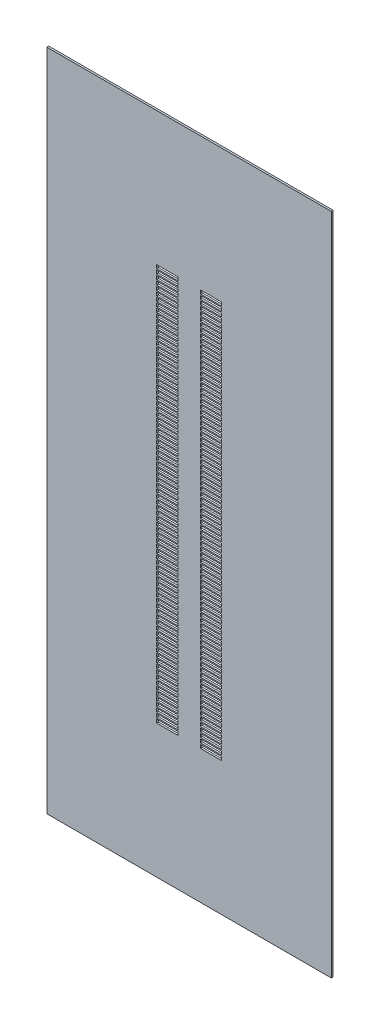
SolidWorks part; units mm, degrees
ref_plane "Front Plane" through (0, 0, 0) normal (0, 0, 1) x (1, 0, 0)
ref_plane "Top Plane" through (0, 0, 0) normal (0, 1, 0) x (1, 0, 0)
ref_plane "Right Plane" through (0, 0, 0) normal (1, 0, 0) x (0, 0, -1)
sketch "Sketch1" plane through (0, 0, 0) normal (0, 0, 1) x (1, 0, 0)
  line L1340 (-1.19, -0.37) -> (-1.19, 0)
  line L1341 (-1.19, 0) -> (-3.41, 0)
  line L1342 (-3.41, 0) -> (-3.41, -0.37)
  line L1343 (-3.41, -0.37) -> (-1.19, -0.37)
  line L2016 (-1.19, 0) -> (1.19, 0) construction
  line L2017 (0, 0) -> (0, -41.87) construction
  line L2018 (1.19, -0.37) -> (1.19, 0)
  line L2019 (3.41, -0.37) -> (1.19, -0.37)
  line L2020 (3.41, 0) -> (3.41, -0.37)
  line L2021 (1.19, 0) -> (3.41, 0)
  line L2022 (1.19, -0.5) -> (3.41, -0.5)
  line L2023 (3.41, -0.5) -> (3.41, -0.87)
  line L2024 (3.41, -0.87) -> (1.19, -0.87)
  line L2025 (1.19, -0.87) -> (1.19, -0.5)
  line L2026 (-1.19, -0.5) -> (-3.41, -0.5)
  line L2027 (-3.41, -0.5) -> (-3.41, -0.87)
  line L2028 (-3.41, -0.87) -> (-1.19, -0.87)
  line L2029 (-1.19, -0.87) -> (-1.19, -0.5)
  line L2030 (1.19, -1) -> (3.41, -1)
  line L2031 (3.41, -1) -> (3.41, -1.37)
  line L2032 (3.41, -1.37) -> (1.19, -1.37)
  line L2033 (1.19, -1.37) -> (1.19, -1)
  line L2034 (-1.19, -1) -> (-3.41, -1)
  line L2035 (-3.41, -1) -> (-3.41, -1.37)
  line L2036 (-3.41, -1.37) -> (-1.19, -1.37)
  line L2037 (-1.19, -1.37) -> (-1.19, -1)
  line L2038 (1.19, -1.5) -> (3.41, -1.5)
  line L2039 (3.41, -1.5) -> (3.41, -1.87)
  line L2040 (3.41, -1.87) -> (1.19, -1.87)
  line L2041 (1.19, -1.87) -> (1.19, -1.5)
  line L2042 (-1.19, -1.5) -> (-3.41, -1.5)
  line L2043 (-3.41, -1.5) -> (-3.41, -1.87)
  line L2044 (-3.41, -1.87) -> (-1.19, -1.87)
  line L2045 (-1.19, -1.87) -> (-1.19, -1.5)
  line L2046 (1.19, -2) -> (3.41, -2)
  line L2047 (3.41, -2) -> (3.41, -2.37)
  line L2048 (3.41, -2.37) -> (1.19, -2.37)
  line L2049 (1.19, -2.37) -> (1.19, -2)
  line L2050 (-1.19, -2) -> (-3.41, -2)
  line L2051 (-3.41, -2) -> (-3.41, -2.37)
  line L2052 (-3.41, -2.37) -> (-1.19, -2.37)
  line L2053 (-1.19, -2.37) -> (-1.19, -2)
  line L2054 (1.19, -2.5) -> (3.41, -2.5)
  line L2055 (3.41, -2.5) -> (3.41, -2.87)
  line L2056 (3.41, -2.87) -> (1.19, -2.87)
  line L2057 (1.19, -2.87) -> (1.19, -2.5)
  line L2058 (-1.19, -2.5) -> (-3.41, -2.5)
  line L2059 (-3.41, -2.5) -> (-3.41, -2.87)
  line L2060 (-3.41, -2.87) -> (-1.19, -2.87)
  line L2061 (-1.19, -2.87) -> (-1.19, -2.5)
  line L2062 (1.19, -3) -> (3.41, -3)
  line L2063 (3.41, -3) -> (3.41, -3.37)
  line L2064 (3.41, -3.37) -> (1.19, -3.37)
  line L2065 (1.19, -3.37) -> (1.19, -3)
  line L2066 (-1.19, -3) -> (-3.41, -3)
  line L2067 (-3.41, -3) -> (-3.41, -3.37)
  line L2068 (-3.41, -3.37) -> (-1.19, -3.37)
  line L2069 (-1.19, -3.37) -> (-1.19, -3)
  line L2070 (1.19, -3.5) -> (3.41, -3.5)
  line L2071 (3.41, -3.5) -> (3.41, -3.87)
  line L2072 (3.41, -3.87) -> (1.19, -3.87)
  line L2073 (1.19, -3.87) -> (1.19, -3.5)
  line L2074 (-1.19, -3.5) -> (-3.41, -3.5)
  line L2075 (-3.41, -3.5) -> (-3.41, -3.87)
  line L2076 (-3.41, -3.87) -> (-1.19, -3.87)
  line L2077 (-1.19, -3.87) -> (-1.19, -3.5)
  line L2078 (1.19, -4) -> (3.41, -4)
  line L2079 (3.41, -4) -> (3.41, -4.37)
  line L2080 (3.41, -4.37) -> (1.19, -4.37)
  line L2081 (1.19, -4.37) -> (1.19, -4)
  line L2082 (-1.19, -4) -> (-3.41, -4)
  line L2083 (-3.41, -4) -> (-3.41, -4.37)
  line L2084 (-3.41, -4.37) -> (-1.19, -4.37)
  line L2085 (-1.19, -4.37) -> (-1.19, -4)
  line L2086 (1.19, -4.5) -> (3.41, -4.5)
  line L2087 (3.41, -4.5) -> (3.41, -4.87)
  line L2088 (3.41, -4.87) -> (1.19, -4.87)
  line L2089 (1.19, -4.87) -> (1.19, -4.5)
  line L2090 (-1.19, -4.5) -> (-3.41, -4.5)
  line L2091 (-3.41, -4.5) -> (-3.41, -4.87)
  line L2092 (-3.41, -4.87) -> (-1.19, -4.87)
  line L2093 (-1.19, -4.87) -> (-1.19, -4.5)
  line L2094 (1.19, -5) -> (3.41, -5)
  line L2095 (3.41, -5) -> (3.41, -5.37)
  line L2096 (3.41, -5.37) -> (1.19, -5.37)
  line L2097 (1.19, -5.37) -> (1.19, -5)
  line L2098 (-1.19, -5) -> (-3.41, -5)
  line L2099 (-3.41, -5) -> (-3.41, -5.37)
  line L2100 (-3.41, -5.37) -> (-1.19, -5.37)
  line L2101 (-1.19, -5.37) -> (-1.19, -5)
  line L2102 (1.19, -5.5) -> (3.41, -5.5)
  line L2103 (3.41, -5.5) -> (3.41, -5.87)
  line L2104 (3.41, -5.87) -> (1.19, -5.87)
  line L2105 (1.19, -5.87) -> (1.19, -5.5)
  line L2106 (-1.19, -5.5) -> (-3.41, -5.5)
  line L2107 (-3.41, -5.5) -> (-3.41, -5.87)
  line L2108 (-3.41, -5.87) -> (-1.19, -5.87)
  line L2109 (-1.19, -5.87) -> (-1.19, -5.5)
  line L2110 (1.19, -6) -> (3.41, -6)
  line L2111 (3.41, -6) -> (3.41, -6.37)
  line L2112 (3.41, -6.37) -> (1.19, -6.37)
  line L2113 (1.19, -6.37) -> (1.19, -6)
  line L2114 (-1.19, -6) -> (-3.41, -6)
  line L2115 (-3.41, -6) -> (-3.41, -6.37)
  line L2116 (-3.41, -6.37) -> (-1.19, -6.37)
  line L2117 (-1.19, -6.37) -> (-1.19, -6)
  line L2118 (1.19, -6.5) -> (3.41, -6.5)
  line L2119 (3.41, -6.5) -> (3.41, -6.87)
  line L2120 (3.41, -6.87) -> (1.19, -6.87)
  line L2121 (1.19, -6.87) -> (1.19, -6.5)
  line L2122 (-1.19, -6.5) -> (-3.41, -6.5)
  line L2123 (-3.41, -6.5) -> (-3.41, -6.87)
  line L2124 (-3.41, -6.87) -> (-1.19, -6.87)
  line L2125 (-1.19, -6.87) -> (-1.19, -6.5)
  line L2126 (1.19, -7) -> (3.41, -7)
  line L2127 (3.41, -7) -> (3.41, -7.37)
  line L2128 (3.41, -7.37) -> (1.19, -7.37)
  line L2129 (1.19, -7.37) -> (1.19, -7)
  line L2130 (-1.19, -7) -> (-3.41, -7)
  line L2131 (-3.41, -7) -> (-3.41, -7.37)
  line L2132 (-3.41, -7.37) -> (-1.19, -7.37)
  line L2133 (-1.19, -7.37) -> (-1.19, -7)
  line L2134 (1.19, -7.5) -> (3.41, -7.5)
  line L2135 (3.41, -7.5) -> (3.41, -7.87)
  line L2136 (3.41, -7.87) -> (1.19, -7.87)
  line L2137 (1.19, -7.87) -> (1.19, -7.5)
  line L2138 (-1.19, -7.5) -> (-3.41, -7.5)
  line L2139 (-3.41, -7.5) -> (-3.41, -7.87)
  line L2140 (-3.41, -7.87) -> (-1.19, -7.87)
  line L2141 (-1.19, -7.87) -> (-1.19, -7.5)
  line L2142 (1.19, -8) -> (3.41, -8)
  line L2143 (3.41, -8) -> (3.41, -8.37)
  line L2144 (3.41, -8.37) -> (1.19, -8.37)
  line L2145 (1.19, -8.37) -> (1.19, -8)
  line L2146 (-1.19, -8) -> (-3.41, -8)
  line L2147 (-3.41, -8) -> (-3.41, -8.37)
  line L2148 (-3.41, -8.37) -> (-1.19, -8.37)
  line L2149 (-1.19, -8.37) -> (-1.19, -8)
  line L2150 (1.19, -8.5) -> (3.41, -8.5)
  line L2151 (3.41, -8.5) -> (3.41, -8.87)
  line L2152 (3.41, -8.87) -> (1.19, -8.87)
  line L2153 (1.19, -8.87) -> (1.19, -8.5)
  line L2154 (-1.19, -8.5) -> (-3.41, -8.5)
  line L2155 (-3.41, -8.5) -> (-3.41, -8.87)
  line L2156 (-3.41, -8.87) -> (-1.19, -8.87)
  line L2157 (-1.19, -8.87) -> (-1.19, -8.5)
  line L2158 (1.19, -9) -> (3.41, -9)
  line L2159 (3.41, -9) -> (3.41, -9.37)
  line L2160 (3.41, -9.37) -> (1.19, -9.37)
  line L2161 (1.19, -9.37) -> (1.19, -9)
  line L2162 (-1.19, -9) -> (-3.41, -9)
  line L2163 (-3.41, -9) -> (-3.41, -9.37)
  line L2164 (-3.41, -9.37) -> (-1.19, -9.37)
  line L2165 (-1.19, -9.37) -> (-1.19, -9)
  line L2166 (1.19, -9.5) -> (3.41, -9.5)
  line L2167 (3.41, -9.5) -> (3.41, -9.87)
  line L2168 (3.41, -9.87) -> (1.19, -9.87)
  line L2169 (1.19, -9.87) -> (1.19, -9.5)
  line L2170 (-1.19, -9.5) -> (-3.41, -9.5)
  line L2171 (-3.41, -9.5) -> (-3.41, -9.87)
  line L2172 (-3.41, -9.87) -> (-1.19, -9.87)
  line L2173 (-1.19, -9.87) -> (-1.19, -9.5)
  line L2174 (1.19, -10) -> (3.41, -10)
  line L2175 (3.41, -10) -> (3.41, -10.37)
  line L2176 (3.41, -10.37) -> (1.19, -10.37)
  line L2177 (1.19, -10.37) -> (1.19, -10)
  line L2178 (-1.19, -10) -> (-3.41, -10)
  line L2179 (-3.41, -10) -> (-3.41, -10.37)
  line L2180 (-3.41, -10.37) -> (-1.19, -10.37)
  line L2181 (-1.19, -10.37) -> (-1.19, -10)
  line L2182 (1.19, -10.5) -> (3.41, -10.5)
  line L2183 (3.41, -10.5) -> (3.41, -10.87)
  line L2184 (3.41, -10.87) -> (1.19, -10.87)
  line L2185 (1.19, -10.87) -> (1.19, -10.5)
  line L2186 (-1.19, -10.5) -> (-3.41, -10.5)
  line L2187 (-3.41, -10.5) -> (-3.41, -10.87)
  line L2188 (-3.41, -10.87) -> (-1.19, -10.87)
  line L2189 (-1.19, -10.87) -> (-1.19, -10.5)
  line L2190 (1.19, -11) -> (3.41, -11)
  line L2191 (3.41, -11) -> (3.41, -11.37)
  line L2192 (3.41, -11.37) -> (1.19, -11.37)
  line L2193 (1.19, -11.37) -> (1.19, -11)
  line L2194 (-1.19, -11) -> (-3.41, -11)
  line L2195 (-3.41, -11) -> (-3.41, -11.37)
  line L2196 (-3.41, -11.37) -> (-1.19, -11.37)
  line L2197 (-1.19, -11.37) -> (-1.19, -11)
  line L2198 (1.19, -11.5) -> (3.41, -11.5)
  line L2199 (3.41, -11.5) -> (3.41, -11.87)
  line L2200 (3.41, -11.87) -> (1.19, -11.87)
  line L2201 (1.19, -11.87) -> (1.19, -11.5)
  line L2202 (-1.19, -11.5) -> (-3.41, -11.5)
  line L2203 (-3.41, -11.5) -> (-3.41, -11.87)
  line L2204 (-3.41, -11.87) -> (-1.19, -11.87)
  line L2205 (-1.19, -11.87) -> (-1.19, -11.5)
  line L2206 (1.19, -12) -> (3.41, -12)
  line L2207 (3.41, -12) -> (3.41, -12.37)
  line L2208 (3.41, -12.37) -> (1.19, -12.37)
  line L2209 (1.19, -12.37) -> (1.19, -12)
  line L2210 (-1.19, -12) -> (-3.41, -12)
  line L2211 (-3.41, -12) -> (-3.41, -12.37)
  line L2212 (-3.41, -12.37) -> (-1.19, -12.37)
  line L2213 (-1.19, -12.37) -> (-1.19, -12)
  line L2214 (1.19, -12.5) -> (3.41, -12.5)
  line L2215 (3.41, -12.5) -> (3.41, -12.87)
  line L2216 (3.41, -12.87) -> (1.19, -12.87)
  line L2217 (1.19, -12.87) -> (1.19, -12.5)
  line L2218 (-1.19, -12.5) -> (-3.41, -12.5)
  line L2219 (-3.41, -12.5) -> (-3.41, -12.87)
  line L2220 (-3.41, -12.87) -> (-1.19, -12.87)
  line L2221 (-1.19, -12.87) -> (-1.19, -12.5)
  line L2222 (1.19, -13) -> (3.41, -13)
  line L2223 (3.41, -13) -> (3.41, -13.37)
  line L2224 (3.41, -13.37) -> (1.19, -13.37)
  line L2225 (1.19, -13.37) -> (1.19, -13)
  line L2226 (-1.19, -13) -> (-3.41, -13)
  line L2227 (-3.41, -13) -> (-3.41, -13.37)
  line L2228 (-3.41, -13.37) -> (-1.19, -13.37)
  line L2229 (-1.19, -13.37) -> (-1.19, -13)
  line L2230 (1.19, -13.5) -> (3.41, -13.5)
  line L2231 (3.41, -13.5) -> (3.41, -13.87)
  line L2232 (3.41, -13.87) -> (1.19, -13.87)
  line L2233 (1.19, -13.87) -> (1.19, -13.5)
  line L2234 (-1.19, -13.5) -> (-3.41, -13.5)
  line L2235 (-3.41, -13.5) -> (-3.41, -13.87)
  line L2236 (-3.41, -13.87) -> (-1.19, -13.87)
  line L2237 (-1.19, -13.87) -> (-1.19, -13.5)
  line L2238 (1.19, -14) -> (3.41, -14)
  line L2239 (3.41, -14) -> (3.41, -14.37)
  line L2240 (3.41, -14.37) -> (1.19, -14.37)
  line L2241 (1.19, -14.37) -> (1.19, -14)
  line L2242 (-1.19, -14) -> (-3.41, -14)
  line L2243 (-3.41, -14) -> (-3.41, -14.37)
  line L2244 (-3.41, -14.37) -> (-1.19, -14.37)
  line L2245 (-1.19, -14.37) -> (-1.19, -14)
  line L2246 (1.19, -14.5) -> (3.41, -14.5)
  line L2247 (3.41, -14.5) -> (3.41, -14.87)
  line L2248 (3.41, -14.87) -> (1.19, -14.87)
  line L2249 (1.19, -14.87) -> (1.19, -14.5)
  line L2250 (-1.19, -14.5) -> (-3.41, -14.5)
  line L2251 (-3.41, -14.5) -> (-3.41, -14.87)
  line L2252 (-3.41, -14.87) -> (-1.19, -14.87)
  line L2253 (-1.19, -14.87) -> (-1.19, -14.5)
  line L2254 (1.19, -15) -> (3.41, -15)
  line L2255 (3.41, -15) -> (3.41, -15.37)
  line L2256 (3.41, -15.37) -> (1.19, -15.37)
  line L2257 (1.19, -15.37) -> (1.19, -15)
  line L2258 (-1.19, -15) -> (-3.41, -15)
  line L2259 (-3.41, -15) -> (-3.41, -15.37)
  line L2260 (-3.41, -15.37) -> (-1.19, -15.37)
  line L2261 (-1.19, -15.37) -> (-1.19, -15)
  line L2262 (1.19, -15.5) -> (3.41, -15.5)
  line L2263 (3.41, -15.5) -> (3.41, -15.87)
  line L2264 (3.41, -15.87) -> (1.19, -15.87)
  line L2265 (1.19, -15.87) -> (1.19, -15.5)
  line L2266 (-1.19, -15.5) -> (-3.41, -15.5)
  line L2267 (-3.41, -15.5) -> (-3.41, -15.87)
  line L2268 (-3.41, -15.87) -> (-1.19, -15.87)
  line L2269 (-1.19, -15.87) -> (-1.19, -15.5)
  line L2270 (1.19, -16) -> (3.41, -16)
  line L2271 (3.41, -16) -> (3.41, -16.37)
  line L2272 (3.41, -16.37) -> (1.19, -16.37)
  line L2273 (1.19, -16.37) -> (1.19, -16)
  line L2274 (-1.19, -16) -> (-3.41, -16)
  line L2275 (-3.41, -16) -> (-3.41, -16.37)
  line L2276 (-3.41, -16.37) -> (-1.19, -16.37)
  line L2277 (-1.19, -16.37) -> (-1.19, -16)
  line L2278 (1.19, -16.5) -> (3.41, -16.5)
  line L2279 (3.41, -16.5) -> (3.41, -16.87)
  line L2280 (3.41, -16.87) -> (1.19, -16.87)
  line L2281 (1.19, -16.87) -> (1.19, -16.5)
  line L2282 (-1.19, -16.5) -> (-3.41, -16.5)
  line L2283 (-3.41, -16.5) -> (-3.41, -16.87)
  line L2284 (-3.41, -16.87) -> (-1.19, -16.87)
  line L2285 (-1.19, -16.87) -> (-1.19, -16.5)
  line L2286 (1.19, -17) -> (3.41, -17)
  line L2287 (3.41, -17) -> (3.41, -17.37)
  line L2288 (3.41, -17.37) -> (1.19, -17.37)
  line L2289 (1.19, -17.37) -> (1.19, -17)
  line L2290 (-1.19, -17) -> (-3.41, -17)
  line L2291 (-3.41, -17) -> (-3.41, -17.37)
  line L2292 (-3.41, -17.37) -> (-1.19, -17.37)
  line L2293 (-1.19, -17.37) -> (-1.19, -17)
  line L2294 (1.19, -17.5) -> (3.41, -17.5)
  line L2295 (3.41, -17.5) -> (3.41, -17.87)
  line L2296 (3.41, -17.87) -> (1.19, -17.87)
  line L2297 (1.19, -17.87) -> (1.19, -17.5)
  line L2298 (-1.19, -17.5) -> (-3.41, -17.5)
  line L2299 (-3.41, -17.5) -> (-3.41, -17.87)
  line L2300 (-3.41, -17.87) -> (-1.19, -17.87)
  line L2301 (-1.19, -17.87) -> (-1.19, -17.5)
  line L2302 (1.19, -18) -> (3.41, -18)
  line L2303 (3.41, -18) -> (3.41, -18.37)
  line L2304 (3.41, -18.37) -> (1.19, -18.37)
  line L2305 (1.19, -18.37) -> (1.19, -18)
  line L2306 (-1.19, -18) -> (-3.41, -18)
  line L2307 (-3.41, -18) -> (-3.41, -18.37)
  line L2308 (-3.41, -18.37) -> (-1.19, -18.37)
  line L2309 (-1.19, -18.37) -> (-1.19, -18)
  line L2310 (1.19, -18.5) -> (3.41, -18.5)
  line L2311 (3.41, -18.5) -> (3.41, -18.87)
  line L2312 (3.41, -18.87) -> (1.19, -18.87)
  line L2313 (1.19, -18.87) -> (1.19, -18.5)
  line L2314 (-1.19, -18.5) -> (-3.41, -18.5)
  line L2315 (-3.41, -18.5) -> (-3.41, -18.87)
  line L2316 (-3.41, -18.87) -> (-1.19, -18.87)
  line L2317 (-1.19, -18.87) -> (-1.19, -18.5)
  line L2318 (1.19, -19) -> (3.41, -19)
  line L2319 (3.41, -19) -> (3.41, -19.37)
  line L2320 (3.41, -19.37) -> (1.19, -19.37)
  line L2321 (1.19, -19.37) -> (1.19, -19)
  line L2322 (-1.19, -19) -> (-3.41, -19)
  line L2323 (-3.41, -19) -> (-3.41, -19.37)
  line L2324 (-3.41, -19.37) -> (-1.19, -19.37)
  line L2325 (-1.19, -19.37) -> (-1.19, -19)
  line L2326 (1.19, -19.5) -> (3.41, -19.5)
  line L2327 (3.41, -19.5) -> (3.41, -19.87)
  line L2328 (3.41, -19.87) -> (1.19, -19.87)
  line L2329 (1.19, -19.87) -> (1.19, -19.5)
  line L2330 (-1.19, -19.5) -> (-3.41, -19.5)
  line L2331 (-3.41, -19.5) -> (-3.41, -19.87)
  line L2332 (-3.41, -19.87) -> (-1.19, -19.87)
  line L2333 (-1.19, -19.87) -> (-1.19, -19.5)
  line L2334 (1.19, -20) -> (3.41, -20)
  line L2335 (3.41, -20) -> (3.41, -20.37)
  line L2336 (3.41, -20.37) -> (1.19, -20.37)
  line L2337 (1.19, -20.37) -> (1.19, -20)
  line L2338 (-1.19, -20) -> (-3.41, -20)
  line L2339 (-3.41, -20) -> (-3.41, -20.37)
  line L2340 (-3.41, -20.37) -> (-1.19, -20.37)
  line L2341 (-1.19, -20.37) -> (-1.19, -20)
  line L2342 (1.19, -20.5) -> (3.41, -20.5)
  line L2343 (3.41, -20.5) -> (3.41, -20.87)
  line L2344 (3.41, -20.87) -> (1.19, -20.87)
  line L2345 (1.19, -20.87) -> (1.19, -20.5)
  line L2346 (-1.19, -20.5) -> (-3.41, -20.5)
  line L2347 (-3.41, -20.5) -> (-3.41, -20.87)
  line L2348 (-3.41, -20.87) -> (-1.19, -20.87)
  line L2349 (-1.19, -20.87) -> (-1.19, -20.5)
  line L2350 (1.19, -21) -> (3.41, -21)
  line L2351 (3.41, -21) -> (3.41, -21.37)
  line L2352 (3.41, -21.37) -> (1.19, -21.37)
  line L2353 (1.19, -21.37) -> (1.19, -21)
  line L2354 (-1.19, -21) -> (-3.41, -21)
  line L2355 (-3.41, -21) -> (-3.41, -21.37)
  line L2356 (-3.41, -21.37) -> (-1.19, -21.37)
  line L2357 (-1.19, -21.37) -> (-1.19, -21)
  line L2358 (1.19, -21.5) -> (3.41, -21.5)
  line L2359 (3.41, -21.5) -> (3.41, -21.87)
  line L2360 (3.41, -21.87) -> (1.19, -21.87)
  line L2361 (1.19, -21.87) -> (1.19, -21.5)
  line L2362 (-1.19, -21.5) -> (-3.41, -21.5)
  line L2363 (-3.41, -21.5) -> (-3.41, -21.87)
  line L2364 (-3.41, -21.87) -> (-1.19, -21.87)
  line L2365 (-1.19, -21.87) -> (-1.19, -21.5)
  line L2366 (1.19, -22) -> (3.41, -22)
  line L2367 (3.41, -22) -> (3.41, -22.37)
  line L2368 (3.41, -22.37) -> (1.19, -22.37)
  line L2369 (1.19, -22.37) -> (1.19, -22)
  line L2370 (-1.19, -22) -> (-3.41, -22)
  line L2371 (-3.41, -22) -> (-3.41, -22.37)
  line L2372 (-3.41, -22.37) -> (-1.19, -22.37)
  line L2373 (-1.19, -22.37) -> (-1.19, -22)
  line L2374 (1.19, -22.5) -> (3.41, -22.5)
  line L2375 (3.41, -22.5) -> (3.41, -22.87)
  line L2376 (3.41, -22.87) -> (1.19, -22.87)
  line L2377 (1.19, -22.87) -> (1.19, -22.5)
  line L2378 (-1.19, -22.5) -> (-3.41, -22.5)
  line L2379 (-3.41, -22.5) -> (-3.41, -22.87)
  line L2380 (-3.41, -22.87) -> (-1.19, -22.87)
  line L2381 (-1.19, -22.87) -> (-1.19, -22.5)
  line L2382 (1.19, -23) -> (3.41, -23)
  line L2383 (3.41, -23) -> (3.41, -23.37)
  line L2384 (3.41, -23.37) -> (1.19, -23.37)
  line L2385 (1.19, -23.37) -> (1.19, -23)
  line L2386 (-1.19, -23) -> (-3.41, -23)
  line L2387 (-3.41, -23) -> (-3.41, -23.37)
  line L2388 (-3.41, -23.37) -> (-1.19, -23.37)
  line L2389 (-1.19, -23.37) -> (-1.19, -23)
  line L2390 (1.19, -23.5) -> (3.41, -23.5)
  line L2391 (3.41, -23.5) -> (3.41, -23.87)
  line L2392 (3.41, -23.87) -> (1.19, -23.87)
  line L2393 (1.19, -23.87) -> (1.19, -23.5)
  line L2394 (-1.19, -23.5) -> (-3.41, -23.5)
  line L2395 (-3.41, -23.5) -> (-3.41, -23.87)
  line L2396 (-3.41, -23.87) -> (-1.19, -23.87)
  line L2397 (-1.19, -23.87) -> (-1.19, -23.5)
  line L2398 (1.19, -24) -> (3.41, -24)
  line L2399 (3.41, -24) -> (3.41, -24.37)
  line L2400 (3.41, -24.37) -> (1.19, -24.37)
  line L2401 (1.19, -24.37) -> (1.19, -24)
  line L2402 (-1.19, -24) -> (-3.41, -24)
  line L2403 (-3.41, -24) -> (-3.41, -24.37)
  line L2404 (-3.41, -24.37) -> (-1.19, -24.37)
  line L2405 (-1.19, -24.37) -> (-1.19, -24)
  line L2406 (1.19, -24.5) -> (3.41, -24.5)
  line L2407 (3.41, -24.5) -> (3.41, -24.87)
  line L2408 (3.41, -24.87) -> (1.19, -24.87)
  line L2409 (1.19, -24.87) -> (1.19, -24.5)
  line L2410 (-1.19, -24.5) -> (-3.41, -24.5)
  line L2411 (-3.41, -24.5) -> (-3.41, -24.87)
  line L2412 (-3.41, -24.87) -> (-1.19, -24.87)
  line L2413 (-1.19, -24.87) -> (-1.19, -24.5)
  line L2414 (1.19, -25) -> (3.41, -25)
  line L2415 (3.41, -25) -> (3.41, -25.37)
  line L2416 (3.41, -25.37) -> (1.19, -25.37)
  line L2417 (1.19, -25.37) -> (1.19, -25)
  line L2418 (-1.19, -25) -> (-3.41, -25)
  line L2419 (-3.41, -25) -> (-3.41, -25.37)
  line L2420 (-3.41, -25.37) -> (-1.19, -25.37)
  line L2421 (-1.19, -25.37) -> (-1.19, -25)
  line L2422 (1.19, -25.5) -> (3.41, -25.5)
  line L2423 (3.41, -25.5) -> (3.41, -25.87)
  line L2424 (3.41, -25.87) -> (1.19, -25.87)
  line L2425 (1.19, -25.87) -> (1.19, -25.5)
  line L2426 (-1.19, -25.5) -> (-3.41, -25.5)
  line L2427 (-3.41, -25.5) -> (-3.41, -25.87)
  line L2428 (-3.41, -25.87) -> (-1.19, -25.87)
  line L2429 (-1.19, -25.87) -> (-1.19, -25.5)
  line L2430 (1.19, -26) -> (3.41, -26)
  line L2431 (3.41, -26) -> (3.41, -26.37)
  line L2432 (3.41, -26.37) -> (1.19, -26.37)
  line L2433 (1.19, -26.37) -> (1.19, -26)
  line L2434 (-1.19, -26) -> (-3.41, -26)
  line L2435 (-3.41, -26) -> (-3.41, -26.37)
  line L2436 (-3.41, -26.37) -> (-1.19, -26.37)
  line L2437 (-1.19, -26.37) -> (-1.19, -26)
  line L2438 (1.19, -26.5) -> (3.41, -26.5)
  line L2439 (3.41, -26.5) -> (3.41, -26.87)
  line L2440 (3.41, -26.87) -> (1.19, -26.87)
  line L2441 (1.19, -26.87) -> (1.19, -26.5)
  line L2442 (-1.19, -26.5) -> (-3.41, -26.5)
  line L2443 (-3.41, -26.5) -> (-3.41, -26.87)
  line L2444 (-3.41, -26.87) -> (-1.19, -26.87)
  line L2445 (-1.19, -26.87) -> (-1.19, -26.5)
  line L2446 (1.19, -27) -> (3.41, -27)
  line L2447 (3.41, -27) -> (3.41, -27.37)
  line L2448 (3.41, -27.37) -> (1.19, -27.37)
  line L2449 (1.19, -27.37) -> (1.19, -27)
  line L2450 (-1.19, -27) -> (-3.41, -27)
  line L2451 (-3.41, -27) -> (-3.41, -27.37)
  line L2452 (-3.41, -27.37) -> (-1.19, -27.37)
  line L2453 (-1.19, -27.37) -> (-1.19, -27)
  line L2454 (1.19, -27.5) -> (3.41, -27.5)
  line L2455 (3.41, -27.5) -> (3.41, -27.87)
  line L2456 (3.41, -27.87) -> (1.19, -27.87)
  line L2457 (1.19, -27.87) -> (1.19, -27.5)
  line L2458 (-1.19, -27.5) -> (-3.41, -27.5)
  line L2459 (-3.41, -27.5) -> (-3.41, -27.87)
  line L2460 (-3.41, -27.87) -> (-1.19, -27.87)
  line L2461 (-1.19, -27.87) -> (-1.19, -27.5)
  line L2462 (1.19, -28) -> (3.41, -28)
  line L2463 (3.41, -28) -> (3.41, -28.37)
  line L2464 (3.41, -28.37) -> (1.19, -28.37)
  line L2465 (1.19, -28.37) -> (1.19, -28)
  line L2466 (-1.19, -28) -> (-3.41, -28)
  line L2467 (-3.41, -28) -> (-3.41, -28.37)
  line L2468 (-3.41, -28.37) -> (-1.19, -28.37)
  line L2469 (-1.19, -28.37) -> (-1.19, -28)
  line L2470 (1.19, -28.5) -> (3.41, -28.5)
  line L2471 (3.41, -28.5) -> (3.41, -28.87)
  line L2472 (3.41, -28.87) -> (1.19, -28.87)
  line L2473 (1.19, -28.87) -> (1.19, -28.5)
  line L2474 (-1.19, -28.5) -> (-3.41, -28.5)
  line L2475 (-3.41, -28.5) -> (-3.41, -28.87)
  line L2476 (-3.41, -28.87) -> (-1.19, -28.87)
  line L2477 (-1.19, -28.87) -> (-1.19, -28.5)
  line L2478 (1.19, -29) -> (3.41, -29)
  line L2479 (3.41, -29) -> (3.41, -29.37)
  line L2480 (3.41, -29.37) -> (1.19, -29.37)
  line L2481 (1.19, -29.37) -> (1.19, -29)
  line L2482 (-1.19, -29) -> (-3.41, -29)
  line L2483 (-3.41, -29) -> (-3.41, -29.37)
  line L2484 (-3.41, -29.37) -> (-1.19, -29.37)
  line L2485 (-1.19, -29.37) -> (-1.19, -29)
  line L2486 (1.19, -29.5) -> (3.41, -29.5)
  line L2487 (3.41, -29.5) -> (3.41, -29.87)
  line L2488 (3.41, -29.87) -> (1.19, -29.87)
  line L2489 (1.19, -29.87) -> (1.19, -29.5)
  line L2490 (-1.19, -29.5) -> (-3.41, -29.5)
  line L2491 (-3.41, -29.5) -> (-3.41, -29.87)
  line L2492 (-3.41, -29.87) -> (-1.19, -29.87)
  line L2493 (-1.19, -29.87) -> (-1.19, -29.5)
  line L2494 (1.19, -30) -> (3.41, -30)
  line L2495 (3.41, -30) -> (3.41, -30.37)
  line L2496 (3.41, -30.37) -> (1.19, -30.37)
  line L2497 (1.19, -30.37) -> (1.19, -30)
  line L2498 (-1.19, -30) -> (-3.41, -30)
  line L2499 (-3.41, -30) -> (-3.41, -30.37)
  line L2500 (-3.41, -30.37) -> (-1.19, -30.37)
  line L2501 (-1.19, -30.37) -> (-1.19, -30)
  line L2502 (1.19, -30.5) -> (3.41, -30.5)
  line L2503 (3.41, -30.5) -> (3.41, -30.87)
  line L2504 (3.41, -30.87) -> (1.19, -30.87)
  line L2505 (1.19, -30.87) -> (1.19, -30.5)
  line L2506 (-1.19, -30.5) -> (-3.41, -30.5)
  line L2507 (-3.41, -30.5) -> (-3.41, -30.87)
  line L2508 (-3.41, -30.87) -> (-1.19, -30.87)
  line L2509 (-1.19, -30.87) -> (-1.19, -30.5)
  line L2510 (1.19, -31) -> (3.41, -31)
  line L2511 (3.41, -31) -> (3.41, -31.37)
  line L2512 (3.41, -31.37) -> (1.19, -31.37)
  line L2513 (1.19, -31.37) -> (1.19, -31)
  line L2514 (-1.19, -31) -> (-3.41, -31)
  line L2515 (-3.41, -31) -> (-3.41, -31.37)
  line L2516 (-3.41, -31.37) -> (-1.19, -31.37)
  line L2517 (-1.19, -31.37) -> (-1.19, -31)
  line L2518 (1.19, -31.5) -> (3.41, -31.5)
  line L2519 (3.41, -31.5) -> (3.41, -31.87)
  line L2520 (3.41, -31.87) -> (1.19, -31.87)
  line L2521 (1.19, -31.87) -> (1.19, -31.5)
  line L2522 (-1.19, -31.5) -> (-3.41, -31.5)
  line L2523 (-3.41, -31.5) -> (-3.41, -31.87)
  line L2524 (-3.41, -31.87) -> (-1.19, -31.87)
  line L2525 (-1.19, -31.87) -> (-1.19, -31.5)
  line L2526 (1.19, -32) -> (3.41, -32)
  line L2527 (3.41, -32) -> (3.41, -32.37)
  line L2528 (3.41, -32.37) -> (1.19, -32.37)
  line L2529 (1.19, -32.37) -> (1.19, -32)
  line L2530 (-1.19, -32) -> (-3.41, -32)
  line L2531 (-3.41, -32) -> (-3.41, -32.37)
  line L2532 (-3.41, -32.37) -> (-1.19, -32.37)
  line L2533 (-1.19, -32.37) -> (-1.19, -32)
  line L2534 (1.19, -32.5) -> (3.41, -32.5)
  line L2535 (3.41, -32.5) -> (3.41, -32.87)
  line L2536 (3.41, -32.87) -> (1.19, -32.87)
  line L2537 (1.19, -32.87) -> (1.19, -32.5)
  line L2538 (-1.19, -32.5) -> (-3.41, -32.5)
  line L2539 (-3.41, -32.5) -> (-3.41, -32.87)
  line L2540 (-3.41, -32.87) -> (-1.19, -32.87)
  line L2541 (-1.19, -32.87) -> (-1.19, -32.5)
  line L2542 (1.19, -33) -> (3.41, -33)
  line L2543 (3.41, -33) -> (3.41, -33.37)
  line L2544 (3.41, -33.37) -> (1.19, -33.37)
  line L2545 (1.19, -33.37) -> (1.19, -33)
  line L2546 (-1.19, -33) -> (-3.41, -33)
  line L2547 (-3.41, -33) -> (-3.41, -33.37)
  line L2548 (-3.41, -33.37) -> (-1.19, -33.37)
  line L2549 (-1.19, -33.37) -> (-1.19, -33)
  line L2550 (1.19, -33.5) -> (3.41, -33.5)
  line L2551 (3.41, -33.5) -> (3.41, -33.87)
  line L2552 (3.41, -33.87) -> (1.19, -33.87)
  line L2553 (1.19, -33.87) -> (1.19, -33.5)
  line L2554 (-1.19, -33.5) -> (-3.41, -33.5)
  line L2555 (-3.41, -33.5) -> (-3.41, -33.87)
  line L2556 (-3.41, -33.87) -> (-1.19, -33.87)
  line L2557 (-1.19, -33.87) -> (-1.19, -33.5)
  line L2558 (1.19, -34) -> (3.41, -34)
  line L2559 (3.41, -34) -> (3.41, -34.37)
  line L2560 (3.41, -34.37) -> (1.19, -34.37)
  line L2561 (1.19, -34.37) -> (1.19, -34)
  line L2562 (-1.19, -34) -> (-3.41, -34)
  line L2563 (-3.41, -34) -> (-3.41, -34.37)
  line L2564 (-3.41, -34.37) -> (-1.19, -34.37)
  line L2565 (-1.19, -34.37) -> (-1.19, -34)
  line L2566 (1.19, -34.5) -> (3.41, -34.5)
  line L2567 (3.41, -34.5) -> (3.41, -34.87)
  line L2568 (3.41, -34.87) -> (1.19, -34.87)
  line L2569 (1.19, -34.87) -> (1.19, -34.5)
  line L2570 (-1.19, -34.5) -> (-3.41, -34.5)
  line L2571 (-3.41, -34.5) -> (-3.41, -34.87)
  line L2572 (-3.41, -34.87) -> (-1.19, -34.87)
  line L2573 (-1.19, -34.87) -> (-1.19, -34.5)
  line L2574 (1.19, -35) -> (3.41, -35)
  line L2575 (3.41, -35) -> (3.41, -35.37)
  line L2576 (3.41, -35.37) -> (1.19, -35.37)
  line L2577 (1.19, -35.37) -> (1.19, -35)
  line L2578 (-1.19, -35) -> (-3.41, -35)
  line L2579 (-3.41, -35) -> (-3.41, -35.37)
  line L2580 (-3.41, -35.37) -> (-1.19, -35.37)
  line L2581 (-1.19, -35.37) -> (-1.19, -35)
  line L2582 (1.19, -35.5) -> (3.41, -35.5)
  line L2583 (3.41, -35.5) -> (3.41, -35.87)
  line L2584 (3.41, -35.87) -> (1.19, -35.87)
  line L2585 (1.19, -35.87) -> (1.19, -35.5)
  line L2586 (-1.19, -35.5) -> (-3.41, -35.5)
  line L2587 (-3.41, -35.5) -> (-3.41, -35.87)
  line L2588 (-3.41, -35.87) -> (-1.19, -35.87)
  line L2589 (-1.19, -35.87) -> (-1.19, -35.5)
  line L2590 (1.19, -36) -> (3.41, -36)
  line L2591 (3.41, -36) -> (3.41, -36.37)
  line L2592 (3.41, -36.37) -> (1.19, -36.37)
  line L2593 (1.19, -36.37) -> (1.19, -36)
  line L2594 (-1.19, -36) -> (-3.41, -36)
  line L2595 (-3.41, -36) -> (-3.41, -36.37)
  line L2596 (-3.41, -36.37) -> (-1.19, -36.37)
  line L2597 (-1.19, -36.37) -> (-1.19, -36)
  line L2598 (1.19, -36.5) -> (3.41, -36.5)
  line L2599 (3.41, -36.5) -> (3.41, -36.87)
  line L2600 (3.41, -36.87) -> (1.19, -36.87)
  line L2601 (1.19, -36.87) -> (1.19, -36.5)
  line L2602 (-1.19, -36.5) -> (-3.41, -36.5)
  line L2603 (-3.41, -36.5) -> (-3.41, -36.87)
  line L2604 (-3.41, -36.87) -> (-1.19, -36.87)
  line L2605 (-1.19, -36.87) -> (-1.19, -36.5)
  line L2606 (1.19, -37) -> (3.41, -37)
  line L2607 (3.41, -37) -> (3.41, -37.37)
  line L2608 (3.41, -37.37) -> (1.19, -37.37)
  line L2609 (1.19, -37.37) -> (1.19, -37)
  line L2610 (-1.19, -37) -> (-3.41, -37)
  line L2611 (-3.41, -37) -> (-3.41, -37.37)
  line L2612 (-3.41, -37.37) -> (-1.19, -37.37)
  line L2613 (-1.19, -37.37) -> (-1.19, -37)
  line L2614 (1.19, -37.5) -> (3.41, -37.5)
  line L2615 (3.41, -37.5) -> (3.41, -37.87)
  line L2616 (3.41, -37.87) -> (1.19, -37.87)
  line L2617 (1.19, -37.87) -> (1.19, -37.5)
  line L2618 (-1.19, -37.5) -> (-3.41, -37.5)
  line L2619 (-3.41, -37.5) -> (-3.41, -37.87)
  line L2620 (-3.41, -37.87) -> (-1.19, -37.87)
  line L2621 (-1.19, -37.87) -> (-1.19, -37.5)
  line L2622 (1.19, -38) -> (3.41, -38)
  line L2623 (3.41, -38) -> (3.41, -38.37)
  line L2624 (3.41, -38.37) -> (1.19, -38.37)
  line L2625 (1.19, -38.37) -> (1.19, -38)
  line L2626 (-1.19, -38) -> (-3.41, -38)
  line L2627 (-3.41, -38) -> (-3.41, -38.37)
  line L2628 (-3.41, -38.37) -> (-1.19, -38.37)
  line L2629 (-1.19, -38.37) -> (-1.19, -38)
  line L2630 (1.19, -38.5) -> (3.41, -38.5)
  line L2631 (3.41, -38.5) -> (3.41, -38.87)
  line L2632 (3.41, -38.87) -> (1.19, -38.87)
  line L2633 (1.19, -38.87) -> (1.19, -38.5)
  line L2634 (-1.19, -38.5) -> (-3.41, -38.5)
  line L2635 (-3.41, -38.5) -> (-3.41, -38.87)
  line L2636 (-3.41, -38.87) -> (-1.19, -38.87)
  line L2637 (-1.19, -38.87) -> (-1.19, -38.5)
  line L2638 (1.19, -39) -> (3.41, -39)
  line L2639 (3.41, -39) -> (3.41, -39.37)
  line L2640 (3.41, -39.37) -> (1.19, -39.37)
  line L2641 (1.19, -39.37) -> (1.19, -39)
  line L2642 (-1.19, -39) -> (-3.41, -39)
  line L2643 (-3.41, -39) -> (-3.41, -39.37)
  line L2644 (-3.41, -39.37) -> (-1.19, -39.37)
  line L2645 (-1.19, -39.37) -> (-1.19, -39)
  line L2646 (1.19, -39.5) -> (3.41, -39.5)
  line L2647 (3.41, -39.5) -> (3.41, -39.87)
  line L2648 (3.41, -39.87) -> (1.19, -39.87)
  line L2649 (1.19, -39.87) -> (1.19, -39.5)
  line L2650 (-1.19, -39.5) -> (-3.41, -39.5)
  line L2651 (-3.41, -39.5) -> (-3.41, -39.87)
  line L2652 (-3.41, -39.87) -> (-1.19, -39.87)
  line L2653 (-1.19, -39.87) -> (-1.19, -39.5)
  line L2654 (1.19, -40) -> (3.41, -40)
  line L2655 (3.41, -40) -> (3.41, -40.37)
  line L2656 (3.41, -40.37) -> (1.19, -40.37)
  line L2657 (1.19, -40.37) -> (1.19, -40)
  line L2658 (-1.19, -40) -> (-3.41, -40)
  line L2659 (-3.41, -40) -> (-3.41, -40.37)
  line L2660 (-3.41, -40.37) -> (-1.19, -40.37)
  line L2661 (-1.19, -40.37) -> (-1.19, -40)
  line L2662 (1.19, -40.5) -> (3.41, -40.5)
  line L2663 (3.41, -40.5) -> (3.41, -40.87)
  line L2664 (3.41, -40.87) -> (1.19, -40.87)
  line L2665 (1.19, -40.87) -> (1.19, -40.5)
  line L2666 (-1.19, -40.5) -> (-3.41, -40.5)
  line L2667 (-3.41, -40.5) -> (-3.41, -40.87)
  line L2668 (-3.41, -40.87) -> (-1.19, -40.87)
  line L2669 (-1.19, -40.87) -> (-1.19, -40.5)
  line L2670 (1.19, -41) -> (3.41, -41)
  line L2671 (3.41, -41) -> (3.41, -41.37)
  line L2672 (3.41, -41.37) -> (1.19, -41.37)
  line L2673 (1.19, -41.37) -> (1.19, -41)
  line L2674 (-1.19, -41) -> (-3.41, -41)
  line L2675 (-3.41, -41) -> (-3.41, -41.37)
  line L2676 (-3.41, -41.37) -> (-1.19, -41.37)
  line L2677 (-1.19, -41.37) -> (-1.19, -41)
  line L2678 (1.19, -41.5) -> (3.41, -41.5)
  line L2679 (3.41, -41.5) -> (3.41, -41.87)
  line L2680 (3.41, -41.87) -> (1.19, -41.87)
  line L2681 (1.19, -41.87) -> (1.19, -41.5)
  line L2682 (-1.19, -41.5) -> (-3.41, -41.5)
  line L2683 (-3.41, -41.5) -> (-3.41, -41.87)
  line L2684 (-3.41, -41.87) -> (-1.19, -41.87)
  line L2685 (-1.19, -41.87) -> (-1.19, -41.5)
  line L2686 (-15, 14.065) -> (15, 14.065)
  line L2687 (15, 14.065) -> (15, -55.935)
  line L2688 (15, -55.935) -> (-15, -55.935)
  line L2689 (-15, -55.935) -> (-15, 14.065)
  line L2690 (-1.19, -41.87) -> (1.19, -41.87) construction
  line L2691 (0, -20.935) -> (7.946, -20.935) construction
  point P676 (0, 0)
  point P677 (0, 0)
  point P679 (-2.3, 0)
  point P680 (2.3, 0)
  dimension "D2" = 84
  dimension "D3" = 0.37
  dimension "D4" = 2.22
  dimension "D5" = 0.5
  dimension "D6" = 70
  dimension "D1" = 4.6
  dimension "D7" = 30
extrude "Boss.-Extru.1" add sketch "Sketch1" along normal blind 0.2
